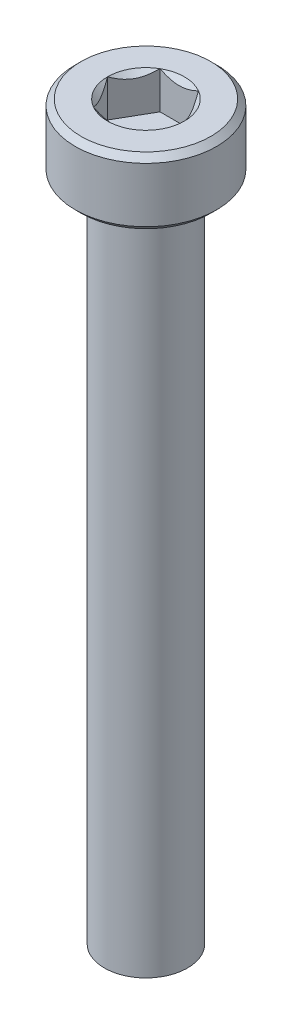
SolidWorks part; units mm, degrees
ref_plane "Front" through (0, 0, 0) normal (0, 0, 1) x (1, 0, 0)
ref_plane "Top" through (0, 0, 0) normal (0, 1, 0) x (1, 0, 0)
ref_plane "Right" through (0, 0, 0) normal (1, 0, 0) x (0, 0, -1)
sketch "Sketch1" plane through (0, 0, 0) normal (0, 1, 0) x (1, 0, 0)
  circle A0 centre (0, 0) radius 4.25
  dimension "D1" = 8.5
extrude "Boss-Extrude1" add sketch "Sketch1" along normal blind 4
sketch "Sketch2" plane through (0, 4, 0) normal (0, 1, 0) x (1, 0, 0)
  line L1 (1.1547, 2) -> (-1.1547, 2)
  line L2 (-1.1547, 2) -> (-2.3094, 0)
  line L3 (-2.3094, 0) -> (-1.1547, -2)
  line L4 (-1.1547, -2) -> (1.1547, -2)
  line L5 (1.1547, -2) -> (2.3094, 0)
  line L6 (2.3094, 0) -> (1.1547, 2)
  circle A0 centre (0, 0) radius 2 construction
  point P10 (0, 2)
  dimension "D1" = 4
extrude "Cut-Extrude1" cut sketch "Sketch2" against normal blind 2.25
sketch "Sketch3" plane through (0, 4, 0) normal (0, 1, 0) x (1, 0, 0)
  circle A0 centre (0, 0) radius 2.3094
extrude "Cut-Extrude2" cut sketch "Sketch3" against normal through all draft 45
chamfer "Chamfer1" distance 0.35 angle 45 2 edges at (0, 0, 4.25) (0, 4, 4.25)
sketch "草图1" plane through (0, 0, 0) normal (0, -1, 0) x (-1, 0, 0)
  circle A0 centre (0, 0) radius 2.5
  dimension "D1" = 5
extrude "凸台-拉伸1" add sketch "草图1" along normal blind 40
